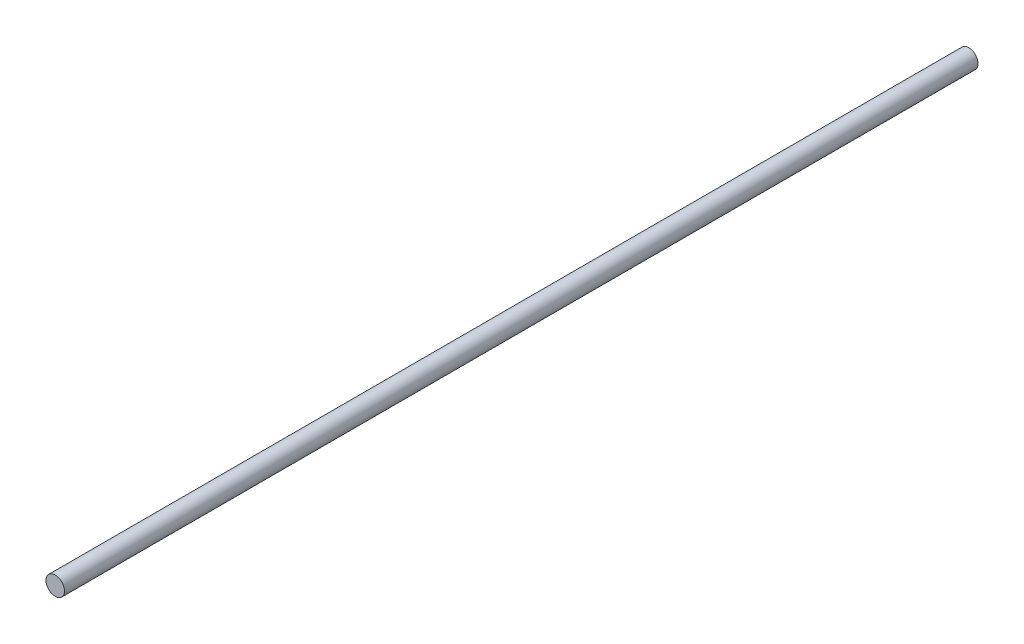
SolidWorks part; units mm, degrees
material "Acero inoxidable fundido"
ref_plane "Alzado" through (0, 0, 0) normal (0, 0, 1) x (1, 0, 0)
ref_plane "Planta" through (0, 0, 0) normal (0, 1, 0) x (1, 0, 0)
ref_plane "Vista lateral" through (0, 0, 0) normal (1, 0, 0) x (0, 0, -1)
sketch "Croquis1" plane through (0, 0, 0) normal (0, 0, 1) x (1, 0, 0)
  circle A0 centre (0, 0) radius 4
  dimension "D1" = 8
extrude "Saliente-Extruir1" add sketch "Croquis1" along normal blind 394
